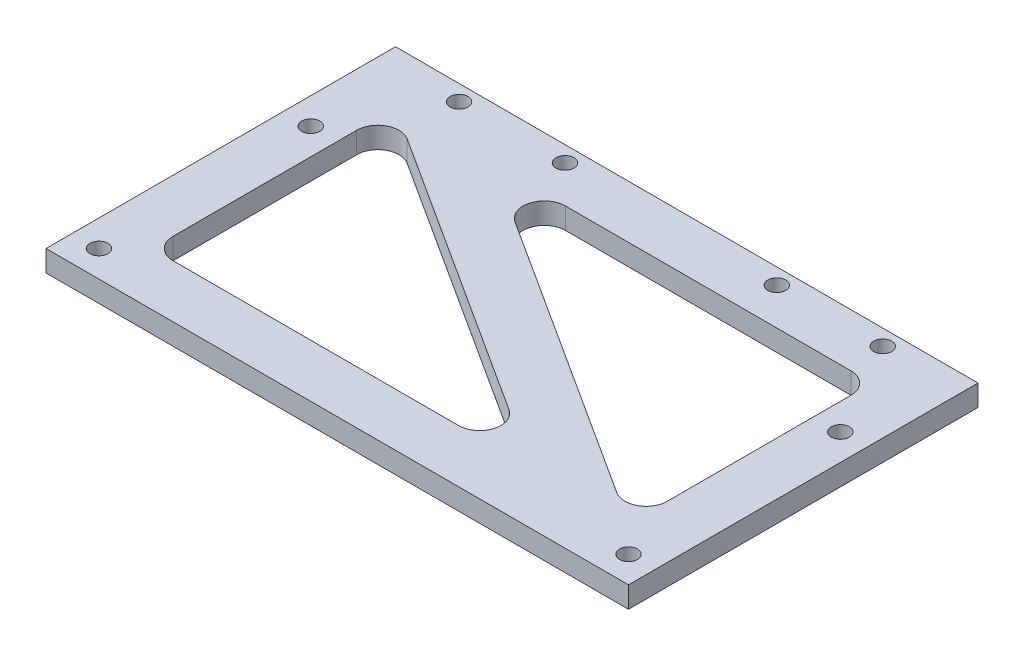
SolidWorks part; units mm, degrees
ref_plane "前视基准面" through (0, 0, 0) normal (0, 0, 1) x (1, 0, 0)
ref_plane "上视基准面" through (0, 0, 0) normal (0, 1, 0) x (1, 0, 0)
ref_plane "右视基准面" through (0, 0, 0) normal (1, 0, 0) x (0, 0, -1)
sketch "草图1" plane through (0, 0, 0) normal (0, 1, 0) x (1, 0, 0)
  line L0 (55, 66) -> (55, 0) construction
  line L1 (0, 0) -> (110, 0)
  line L2 (0, 0) -> (0, 66)
  line L3 (0, 66) -> (110, 66)
  line L4 (110, 0) -> (110, 66)
  line L5 (5, 0) -> (5, 5) construction
  line L6 (5, 5) -> (5, 45) construction
  line L7 (15, 66) -> (15, 63) construction
  line L8 (15, 63) -> (35, 63) construction
  circle A0 centre (5, 45) radius 1.7
  circle A1 centre (5, 5) radius 1.7
  circle A2 centre (105, 5) radius 1.7
  circle A3 centre (105, 45) radius 1.7
  circle A4 centre (15, 63) radius 1.7
  circle A5 centre (35, 63) radius 1.7
  circle A6 centre (75, 63) radius 1.7
  circle A7 centre (95, 63) radius 1.7
  dimension "D1" = 3.4
  dimension "D4" = 100
  dimension "D5" = 5
  dimension "D7" = 3.4
  dimension "D10" = 40
  dimension "D3" = 18
  dimension "D2" = 110
  dimension "D6" = 40
  dimension "D8" = 20
  dimension "D9" = 3
extrude "凸台-拉伸1" add sketch "草图1" along normal blind 4
sketch "草图2" plane through (0, 0, 0) normal (0, -1, 0) x (1, 0, 0)
  line L0 (100, -56) -> (100, -10)
  line L1 (100, -10) -> (28.4851, -56)
  line L2 (28.4851, -56) -> (100, -56)
  line L3 (10, -56) -> (81.5149, -10)
  line L4 (81.5149, -10) -> (10, -10)
  line L5 (10, -10) -> (10, -56)
  line L6 (0, -66) -> (0, 0) construction
  line L7 (0, 0) -> (110, 0) construction
  line L8 (110, -66) -> (0, -66) construction
  line L9 (110, 0) -> (110, -66) construction
  dimension "D1" = 10
  dimension "D2" = 10
  dimension "D3" = 10
  dimension "D4" = 10
  dimension "D5" = 10
extrude "切除-拉伸1" cut sketch "草图2" against normal blind 10
fillet "圆角1" radius 4 6 edges at (81.5149, 2, -10) (10, 2, -10) (10, 2, -56) (100, 2, -10) (28.4851, 2, -56) (100, 2, -56)
